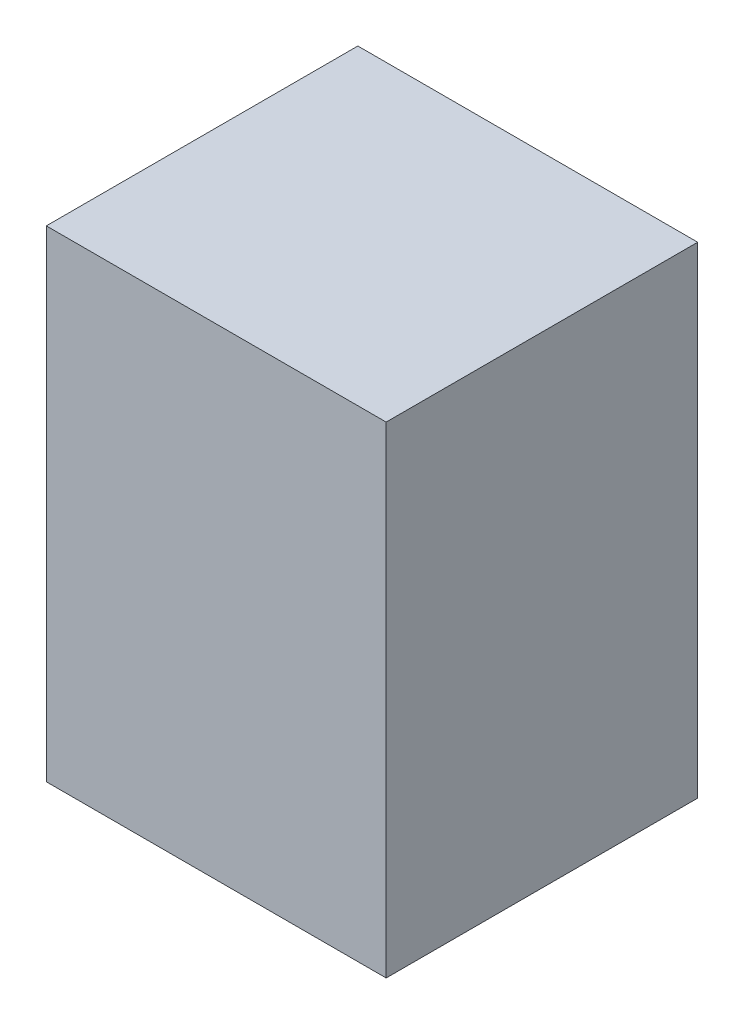
SolidWorks part; units mm, degrees
ref_plane "Front Plane" through (0, 0, 0) normal (0, 0, 1) x (1, 0, 0)
ref_plane "Top Plane" through (0, 0, 0) normal (0, 1, 0) x (1, 0, 0)
ref_plane "Right Plane" through (0, 0, 0) normal (1, 0, 0) x (0, 0, -1)
ref_plane "Plane1" through (0, 0, -5.5) normal (0, 0, -1) x (-1, 0, 0)
sketch "Sketch1" plane through (0, 0, -5.5) normal (0, 0, -1) x (-1, 0, 0)
  line L0 (-6, 0) -> (6, 0)
  line L1 (6, 0) -> (6, 17)
  line L2 (6, 17) -> (-6, 17)
  line L3 (-6, 17) -> (-6, 0)
extrude "Boss-Extrude1" add sketch "Sketch1" against normal blind 11
sketch "Sketch2" plane through (0, 0, 0) normal (0, -1, 0) x (1, 0, 0)
  line L0 (4.1, 4.1) -> (-4.1, 4.1)
  line L1 (-4.1, 4.1) -> (-4.1, -4.1)
  line L2 (-4.1, -4.1) -> (4.1, -4.1)
  line L3 (4.1, -4.1) -> (4.1, 4.1)
extrude "Cut-Extrude1" cut sketch "Sketch2" against normal blind 15
sketch "Sketch3" plane through (0, 15, 0) normal (0, -1, 0) x (1, 0, 0)
  line L0 (-3, 1.5) -> (3, 1.5)
  line L1 (3, 1.5) -> (3, -1.5)
  line L2 (3, -1.5) -> (-3, -1.5)
  line L3 (-3, -1.5) -> (-3, 1.5)
extrude "Boss-Extrude2" add sketch "Sketch3" along normal blind 15
chamfer "Chamfer1" distance 1.1201 angle 48.381 1 edges at (4.1, 7.5, 4.1)
chamfer "Chamfer2" distance 1.2608 angle 41.619 1 edges at (-4.1, 7.5, 4.1)
